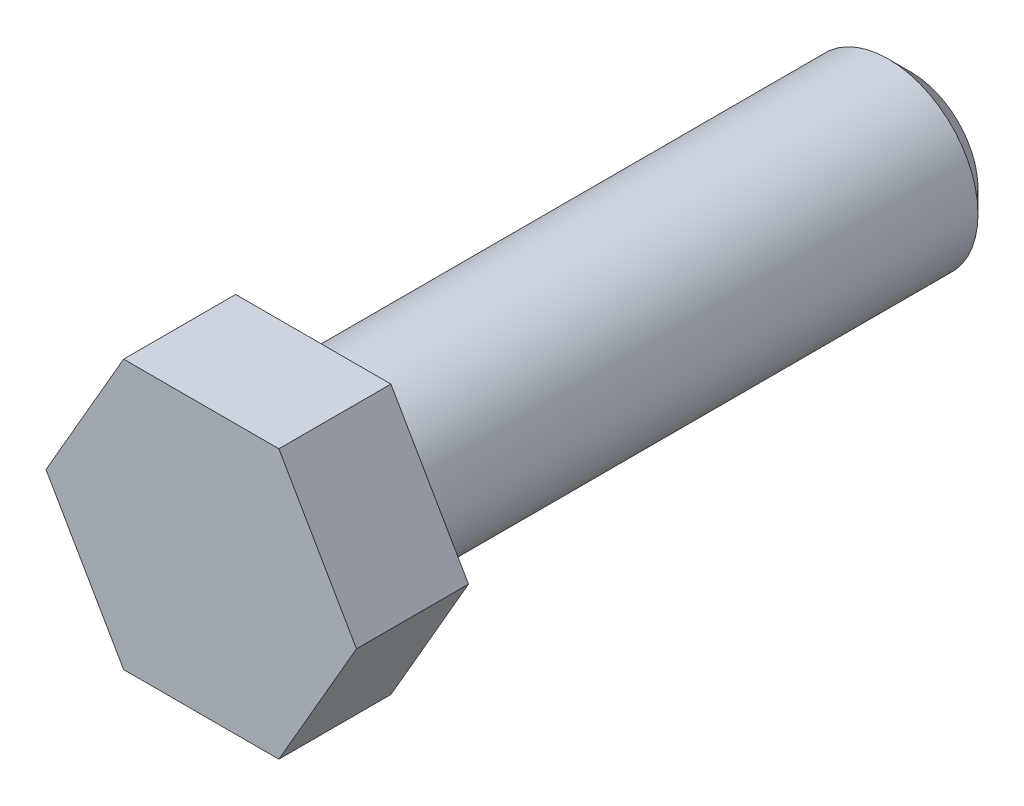
SolidWorks part; units mm, degrees
ref_plane "Plane1" through (0, 0, 0) normal (0, 0, 1) x (1, 0, 0)
ref_plane "MSC_PF1" through (0, 0, 0) normal (0, 1, 0) x (1, 0, 0)
ref_plane "Plane3" through (0, 0, 0) normal (1, 0, 0) x (0, 0, -1)
sketch "Sketch1" plane through (0, 0, 0) normal (0, 0, 1) x (1, 0, 0)
  line L0 (0, 0) -> (1, 0) construction
  line L1 (-5.1962, 9) -> (5.1962, 9)
  line L2 (-5.1962, -9) -> (5.1962, -9)
  line L3 (5.1962, 9) -> (10.3923, 0)
  line L4 (10.3923, 0) -> (5.1962, -9)
  line L5 (-5.1962, 9) -> (-10.3923, 0)
  line L6 (-10.3923, 0) -> (-5.1962, -9)
  circle A0 centre (0, 0) radius 9 construction
  dimension "P" = 1
  dimension "s" = 18
extrude "Base-Extrude" add sketch "Sketch1" along normal blind 7.5
sketch "Sketch3" plane through (0, 0, 0) normal (0, 0, -1) x (-1, 0, 0)
  circle A0 centre (0, 0) radius 6
  dimension "_d" = 12
extrude "Boss-Extrude1" add sketch "Sketch3" along normal blind 40
cosmetic thread "Условное изображение резьбы2" parameters "D2"=11
chamfer "Chamfer1" distance 1.5 angle 45 1 edges at (-6, 0, -40)
